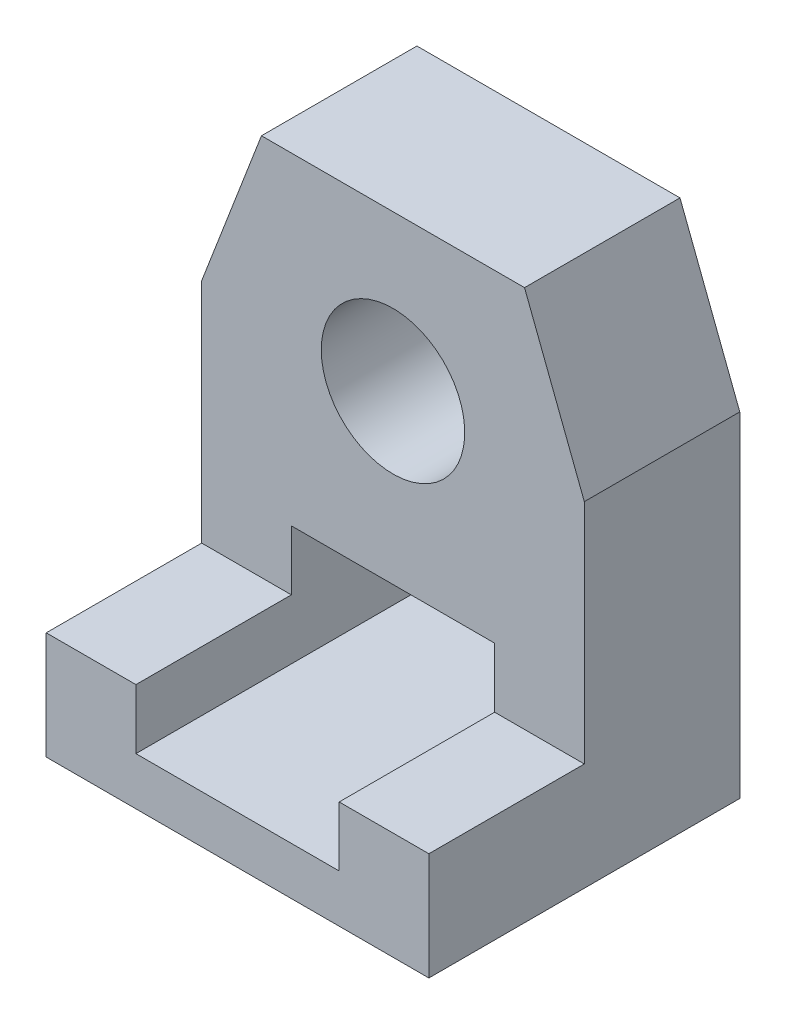
SolidWorks part; units mm, degrees
ref_plane "前视基准面" through (0, 0, 0) normal (0, 0, 1) x (1, 0, 0)
ref_plane "上视基准面" through (0, 0, 0) normal (0, 1, 0) x (1, 0, 0)
ref_plane "右视基准面" through (0, 0, 0) normal (1, 0, 0) x (0, 0, -1)
other "Configuration Table"
sketch "草图1" plane through (0, 0, 0) normal (0, 0, 1) x (1, 0, 0)
  line L0 (-300.2393, 0) -> (14711.7233, 0) construction
  line L1 (0, -300.2393) -> (0, 14711.7233) construction
  line L2 (-11, 13) -> (11, 13)
  line L3 (11, 13) -> (16, 0)
  line L4 (16, 0) -> (16, -28)
  line L5 (16, -28) -> (-16, -28)
  line L6 (-8.5, -24) -> (8.5, -24)
  line L7 (8.5, -24) -> (8.5, -14)
  line L8 (8.5, -14) -> (-8.5, -14)
  line L9 (-8.5, -24) -> (-8.5, -14)
  line L10 (-16, 0) -> (-16, -28)
  line L11 (-11, 13) -> (-16, 0)
  line L12 (-16, -19) -> (16, -19) construction
  circle A0 centre (0, 0) radius 6
  point P17 (0, -14)
  point P18 (0, -24)
  point P19 (0, -28)
  point P21 (0, 13)
  dimension "D1" = 22
  dimension "D9" = 12
  dimension "D2" = 28
  dimension "D3" = 41
  dimension "D4" = 32
  dimension "D5" = 17
  dimension "D6" = 10
  dimension "D7" = 5
  dimension "D8" = 9
extrude "凸台-拉伸1" add sketch "草图1" along normal blind 13
sketch "草图2" plane through (0, 0, 13) normal (0, 0, 1) x (1, 0, 0)
  line L0 (-16, -19) -> (16, -19)
  line L1 (-16, 0) -> (-16, -28) construction
  line L2 (16, -28) -> (16, 0) construction
  line L3 (-16, -28) -> (16, -28) construction
  line L4 (-8.5, -14) -> (-8.5, -24) construction
  line L5 (-8.5, -19) -> (8.5, -19)
  line L6 (-8.5, -19) -> (-8.5, -24)
  line L7 (-8.5, -24) -> (8.5, -24)
  line L8 (8.5, -19) -> (8.5, -24)
  line L10 (-16, -19) -> (16, -19)
  line L11 (-16, -19) -> (-16, -28)
  line L12 (-16, -28) -> (16, -28)
  line L13 (16, -19) -> (16, -28)
  line M6 (-16, 0) -> (-16, -28)
  line M7 (-16, -28) -> (16, -28)
  line M8 (16, -28) -> (16, 0)
  line M9 (8.5, -14) -> (8.5, -24)
  line M10 (8.5, -24) -> (-8.5, -24)
  line M11 (-8.5, -24) -> (-8.5, -14)
  dimension "D1" = 9
extrude "凸台-拉伸2" add sketch "草图2" along normal blind 13 contours L0 M6 M7 M8 M9 M10 M11
